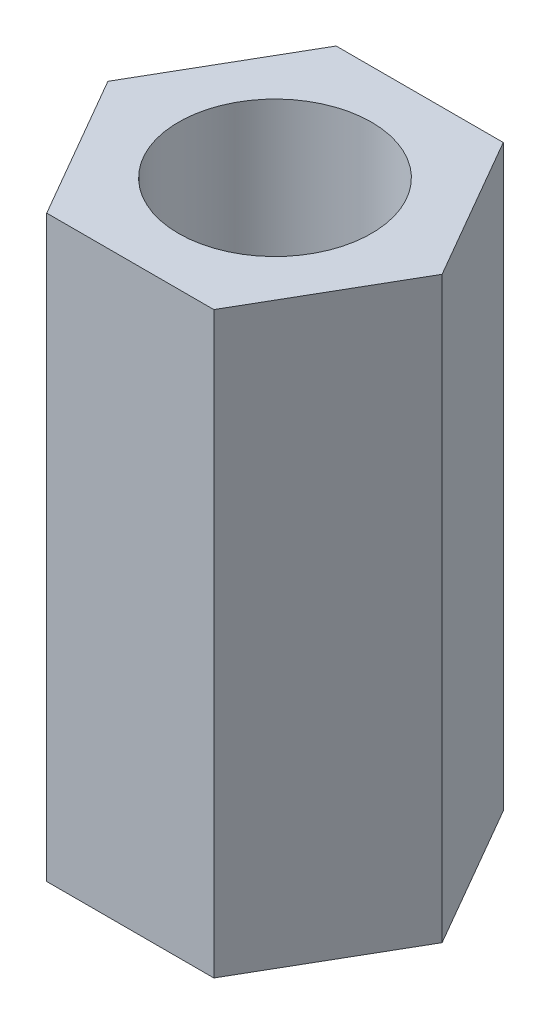
SolidWorks part; units mm, degrees
material "黄铜"
ref_plane "前视基准面" through (0, 0, 0) normal (0, 0, 1) x (1, 0, 0)
ref_plane "上视基准面" through (0, 0, 0) normal (0, 1, 0) x (1, 0, 0)
ref_plane "右视基准面" through (0, 0, 0) normal (1, 0, 0) x (0, 0, -1)
sketch "草图1" plane through (0, 0, 0) normal (0, 1, 0) x (1, 0, 0)
  line L1 (1.7321, 0) -> (0.866, 1.5)
  line L2 (0.866, 1.5) -> (-0.866, 1.5)
  line L3 (-0.866, 1.5) -> (-1.7321, 0)
  line L4 (-1.7321, 0) -> (-0.866, -1.5)
  line L5 (-0.866, -1.5) -> (0.866, -1.5)
  line L6 (0.866, -1.5) -> (1.7321, 0)
  circle A0 centre (0, 0) radius 1.5 construction
  dimension "D1" = 3
extrude "凸台-拉伸1" add sketch "草图1" along normal blind 6
sketch "草图2" plane through (0, 6, 0) normal (0, 1, 0) x (1, 0, 0)
  circle A0 centre (0, 0) radius 1
  dimension "D1" = 2
extrude "切除-拉伸1" cut sketch "草图2" against normal through all
